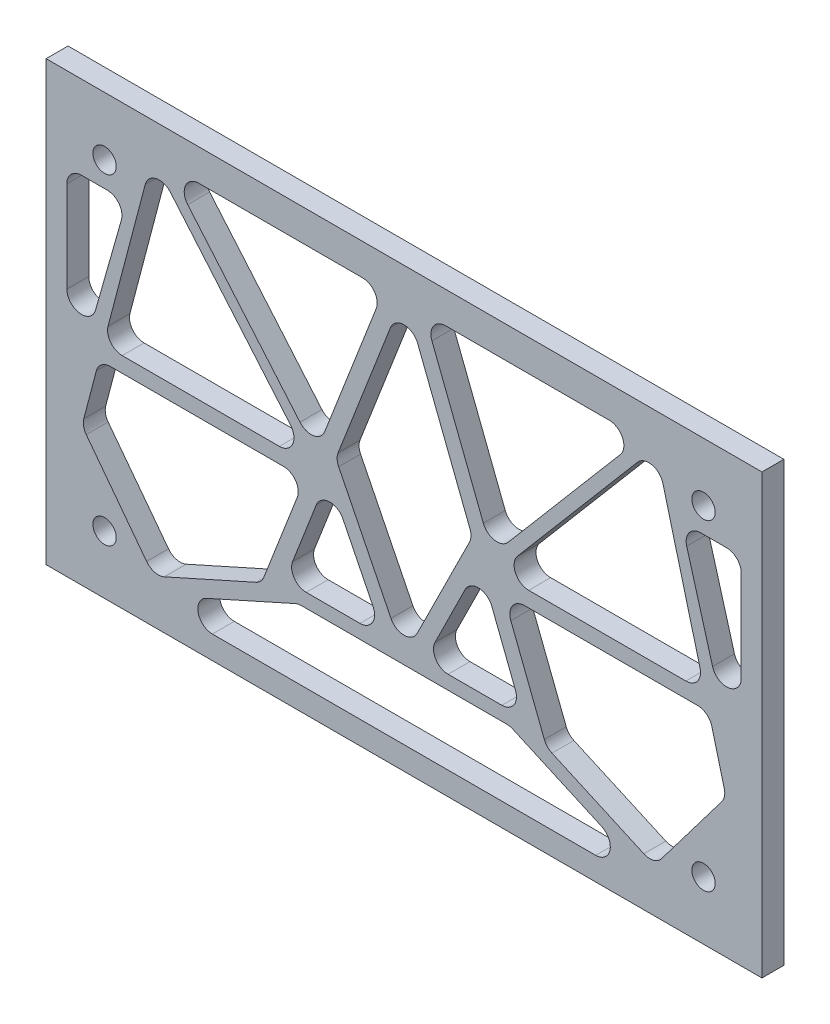
SolidWorks part; units mm, degrees
material "Thornel Mat VMA"
ref_plane "前视基准面" through (0, 0, 0) normal (0, 0, 1) x (1, 0, 0)
ref_plane "上视基准面" through (0, 0, 0) normal (0, 1, 0) x (1, 0, 0)
ref_plane "右视基准面" through (0, 0, 0) normal (1, 0, 0) x (0, 0, -1)
other "Configuration Table"
sketch "草图1" plane through (0, 0, 0) normal (0, 0, 1) x (1, 0, 0)
  line L0 (49, 0) -> (49, 82.1055) construction
  line L1 (0, 0) -> (98, 0)
  line L2 (0, 0) -> (0, 60)
  line L3 (0, 60) -> (98, 60)
  line L4 (98, 0) -> (98, 60)
  line L5 (0, 30) -> (168.6186, 30) construction
  line L36 (49, 56.4615) -> (39.6529, 32.4371)
  line L37 (32.685, 14.528) -> (46.1913, 14.528)
  line L38 (65.315, 14.528) -> (59.3744, 29.7969)
  line L39 (51.7544, 55.676) -> (61.0747, 31.7208)
  line L40 (61.0747, 31.7208) -> (81.4174, 55.676)
  line L41 (81.4174, 55.676) -> (51.7544, 55.676)
  line L42 (83.4614, 55.5737) -> (61.7442, 30)
  line L43 (62.5606, 27.9016) -> (68.5036, 12.6266)
  line L44 (68.5036, 12.6266) -> (83.2821, 5.9983)
  line L45 (83.2821, 5.9983) -> (93.0919, 18.9425)
  line L46 (93.0919, 18.9425) -> (90.7365, 27.9016)
  line L47 (34.5162, 12.6266) -> (63.4838, 12.6266)
  line L53 (63.4838, 12.6266) -> (84.5839, 3.163)
  line L54 (84.5839, 3.163) -> (13.4161, 3.163)
  line L55 (13.4161, 3.163) -> (34.5162, 12.6266)
  line L61 (14.7179, 5.9983) -> (4.9081, 18.9425)
  line L62 (29.4964, 12.6266) -> (14.7179, 5.9983)
  line L63 (35.4394, 27.9016) -> (29.4964, 12.6266)
  line L64 (14.5386, 55.5737) -> (36.2558, 30)
  line L65 (4.9081, 18.9425) -> (7.2635, 27.9016)
  line L66 (36.9253, 31.7208) -> (16.5826, 55.676)
  line L67 (46.2456, 55.676) -> (36.9253, 31.7208)
  line L68 (16.5826, 55.676) -> (46.2456, 55.676)
  line L69 (49, 13.6457) -> (39.6529, 32.4371)
  line L70 (49, 13.6457) -> (58.3471, 32.4371)
  line L71 (38.6256, 29.7969) -> (46.1913, 14.528)
  line L72 (59.3744, 29.7969) -> (51.8087, 14.528)
  line L73 (51.8087, 14.528) -> (65.315, 14.528)
  line L74 (38.6256, 29.7969) -> (32.685, 14.528)
  line L75 (58.3471, 32.4371) -> (49, 56.4615)
  line L76 (2.8399, 48.592) -> (11.0242, 48.592)
  line L77 (11.0242, 48.592) -> (2.8399, 19.7021)
  line L78 (2.8399, 19.7021) -> (2.8399, 48.592)
  line L79 (86.9758, 48.592) -> (95.1601, 19.7021)
  line L80 (95.1601, 48.592) -> (86.9758, 48.592)
  line L81 (95.1601, 19.7021) -> (95.1601, 48.592)
  line L82 (36.2558, 30) -> (7.8152, 30)
  line L83 (7.2635, 27.9016) -> (35.4394, 27.9016)
  line L84 (7.8152, 30) -> (14.5386, 55.5737)
  line L85 (61.7442, 30) -> (90.1848, 30)
  line L86 (62.5606, 27.9016) -> (90.7365, 27.9016)
  line L87 (90.1848, 30) -> (83.4614, 55.5737)
  circle A0 centre (8, 8) radius 1.6
  circle A1 centre (90, 8) radius 1.6
  circle A2 centre (90, 52) radius 1.6
  circle A3 centre (8, 52) radius 1.6
  dimension "D4" = 3.2
  dimension "D1" = 98
  dimension "D2" = 60
  dimension "D3" = 8
  dimension "D5" = 8
extrude "凸台-拉伸1" add sketch "草图1" along normal blind 3
fillet "圆角4" radius 2 42 edges at (11.0242, 48.592, 1.5) (83.2821, 5.9983, 1.5) (93.0919, 18.9425, 1.5) (84.5839, 3.163, 1.5) (63.4838, 12.6266, 1.5) (34.5162, 12.6266, 1.5) (13.4161, 3.163, 1.5) (29.4964, 12.6266, 1.5) (14.7179, 5.9983, 1.5) (4.9081, 18.9425, 1.5) (46.1913, 14.528, 1.5) (32.685, 14.528, 1.5) (38.6256, 29.7969, 1.5) (65.315, 14.528, 1.5) (51.8087, 14.528, 1.5) (59.3744, 29.7969, 1.5) (68.5036, 12.6266, 1.5) (81.4174, 55.676, 1.5) (51.7544, 55.676, 1.5) (61.0747, 31.7208, 1.5) (49, 13.6457, 1.5) (49, 56.4615, 1.5) (39.6529, 32.4371, 1.5) (58.3471, 32.4371, 1.5) (36.9253, 31.7208, 1.5) (16.5826, 55.676, 1.5) (46.2456, 55.676, 1.5) (95.1601, 48.592, 1.5) (86.9758, 48.592, 1.5) (95.1601, 19.7021, 1.5) (2.8399, 19.7021, 1.5) (2.8399, 48.592, 1.5) (62.5606, 27.9016, 1.5) (90.7365, 27.9016, 1.5) (90.1848, 30, 1.5) (61.7442, 30, 1.5) (35.4394, 27.9016, 1.5) (7.2635, 27.9016, 1.5) (7.8152, 30, 1.5) (36.2558, 30, 1.5) (83.4614, 55.5737, 1.5) (14.5386, 55.5737, 1.5)
